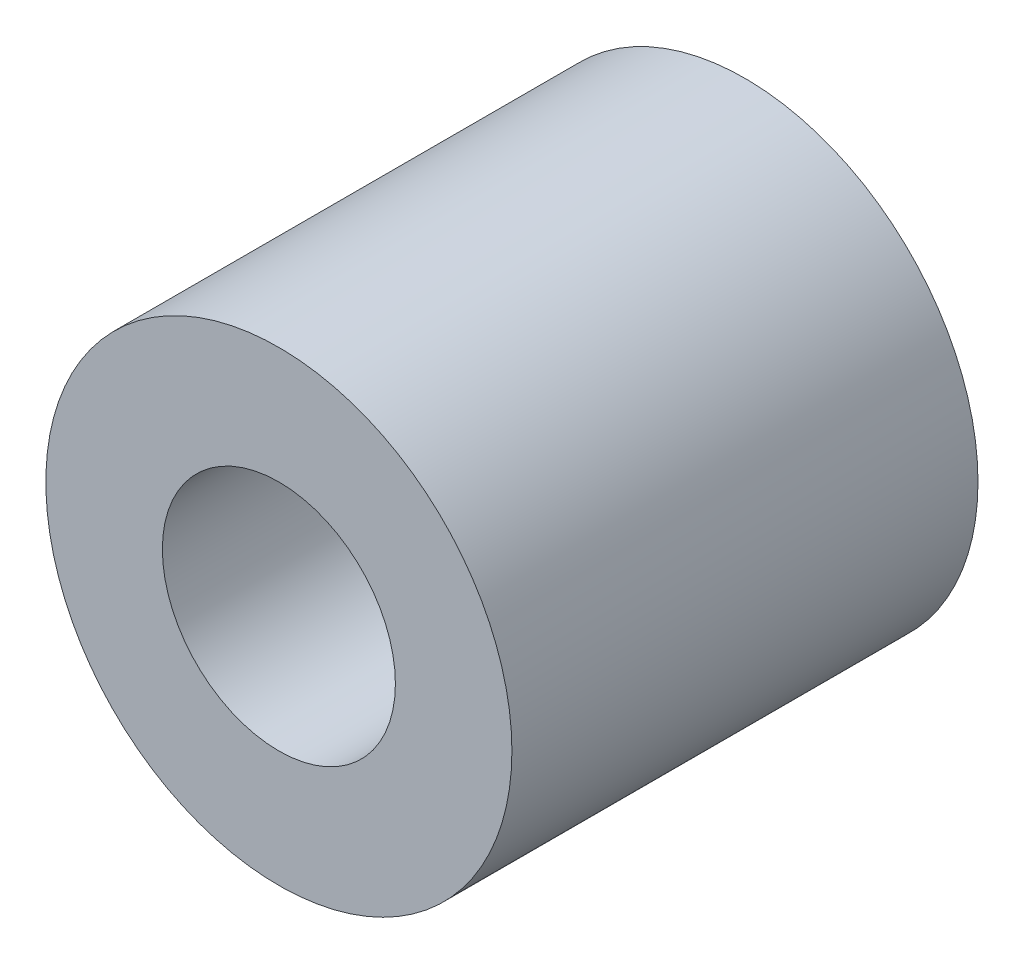
SolidWorks part; units mm, degrees
ref_plane "前视基准面" through (0, 0, 0) normal (0, 0, 1) x (1, 0, 0)
ref_plane "上视基准面" through (0, 0, 0) normal (0, 1, 0) x (1, 0, 0)
ref_plane "右视基准面" through (0, 0, 0) normal (1, 0, 0) x (0, 0, -1)
sketch "草图1" plane through (0, 0, 0) normal (0, 0, 1) x (1, 0, 0)
  circle A0 centre (0, 0) radius 2
  circle A1 centre (0, 0) radius 1
extrude "凸台-拉伸1" add sketch "草图1" along normal blind 4
